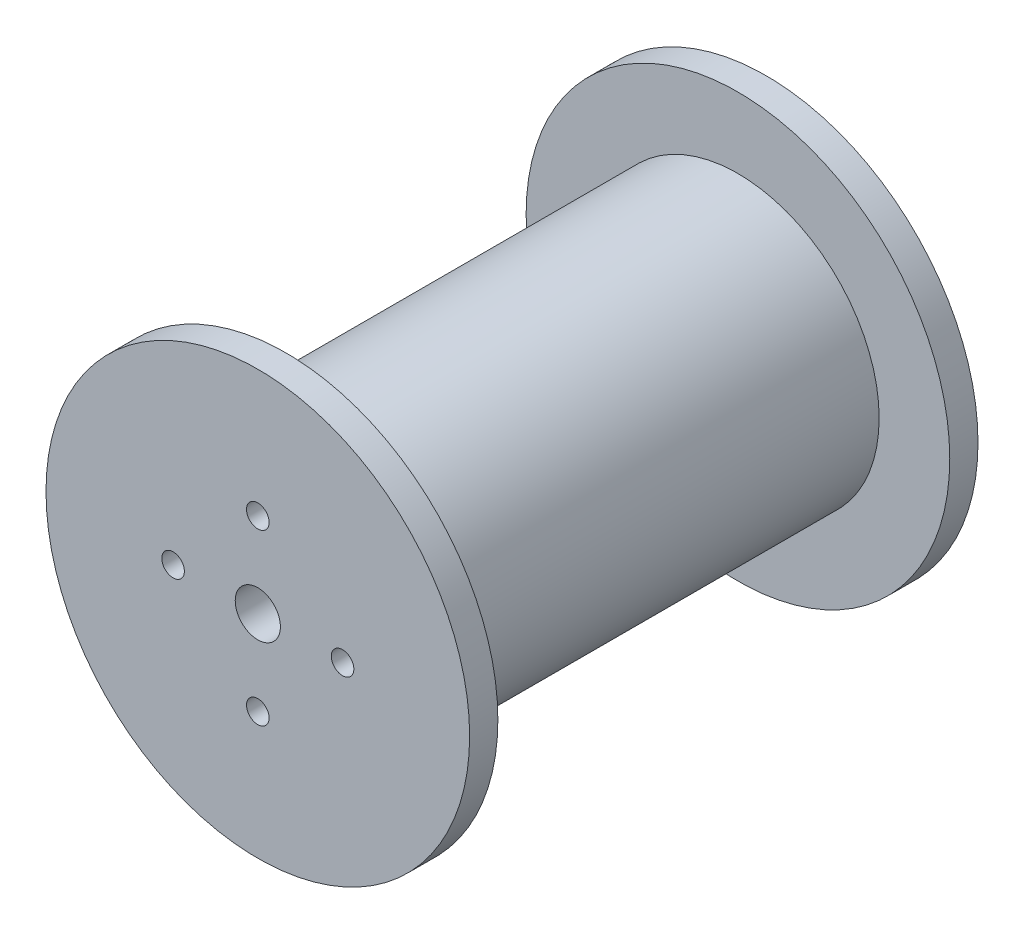
SolidWorks part; units mm, degrees
material "50%PLA"
ref_plane "Front Plane" through (0, 0, 0) normal (0, 0, 1) x (1, 0, 0)
ref_plane "Top Plane" through (0, 0, 0) normal (0, 1, 0) x (1, 0, 0)
ref_plane "Right Plane" through (0, 0, 0) normal (1, 0, 0) x (0, 0, -1)
sketch "Sketch1" plane through (0, 0, 0) normal (0, 0, 1) x (1, 0, 0)
  circle A0 centre (0, 0) radius 25
  dimension "D1" = 50
extrude "Boss-Extrude1" add sketch "Sketch1" along normal blind 80
sketch "Sketch2" plane through (0, 0, 80) normal (0, 0, 1) x (1, 0, 0)
  circle A0 centre (0, 0) radius 37.5
  dimension "D1" = 75
extrude "Boss-Extrude2" add sketch "Sketch2" along normal blind 5
sketch "Sketch3" plane through (0, 0, 0) normal (0, 0, -1) x (-1, 0, 0)
  circle A0 centre (0, 0) radius 37.5
extrude "Boss-Extrude3" add sketch "Sketch3" along normal blind 5
sketch "Sketch4" plane through (0, 0, -5) normal (0, 0, -1) x (-1, 0, 0)
  circle A0 centre (0, 0) radius 4
  circle A2 centre (0, 15) radius 2
  circle A3 centre (15, 0) radius 2
  circle A4 centre (0, -15) radius 2
  circle A5 centre (-15, 0) radius 2
  point P15 (0, 0)
  dimension "D1" = 8
  dimension "D3" = 4
  dimension "D4" = 4
extrude "Cut-Extrude1" cut sketch "Sketch4" against normal through all
